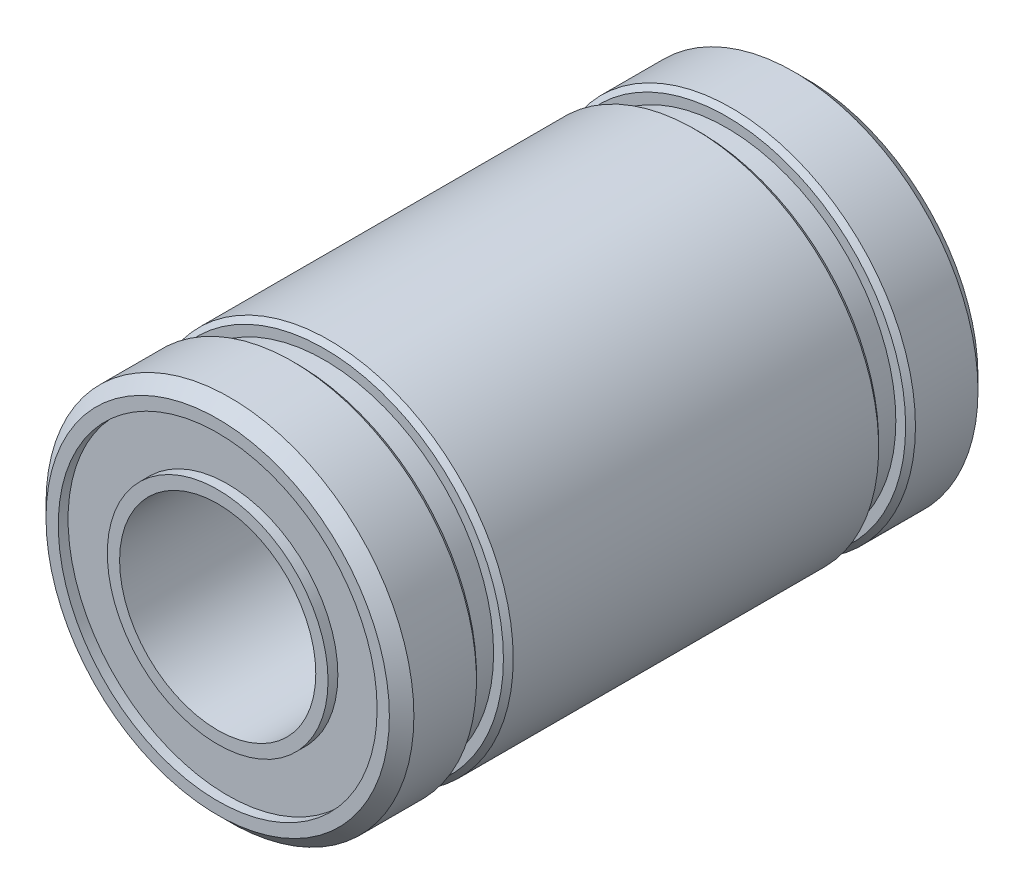
SolidWorks part; units mm, degrees
ref_plane "Front Plane" through (0, 0, 0) normal (0, 0, 1) x (1, 0, 0)
ref_plane "Top Plane" through (0, 0, 0) normal (0, 1, 0) x (1, 0, 0)
ref_plane "Right Plane" through (0, 0, 0) normal (1, 0, 0) x (0, 0, -1)
sketch "Sketch1" plane through (0, 0, 0) normal (0, 0, 1) x (1, 0, 0)
  circle A0 centre (0, 0) radius 4
  circle A1 centre (0, 0) radius 7.5
  dimension "D1" = 8
  dimension "D2" = 15
extrude "Boss-Extrude1" add sketch "Sketch1" along normal blind 24
sketch "Sketch2" plane through (0, 0, 24) normal (0, 0, 1) x (1, 0, 0)
  circle A0 centre (0, 0) radius 4.5
  circle A1 centre (0, 0) radius 6.5
  dimension "D1" = 13
  dimension "9" = 9
extrude "Cut-Extrude1" cut sketch "Sketch2" against normal blind 0.4
ref_plane "Plane1" through (0, 0, 12) normal (0, 0, 1) x (1, 0, 0)
mirror "Mirror1" about plane through (0, 0, 12) normal (0, 0, 1) of "Cut-Extrude1"
sketch "Sketch3" plane through (0, 0, 0) normal (1, 0, 0) x (0, 0, -1)
  line L0 (0, 7.5) -> (-24, 7.5) construction
  line L1 (-20.75, 7.5) -> (-19.65, 7.5)
  line L2 (-20.75, 7.5) -> (-20.75, 6.9)
  line L3 (-20.75, 6.9) -> (-19.65, 6.9)
  line L4 (-19.65, 7.5) -> (-19.65, 6.9)
  line L5 (-24, 7.5) -> (-24, -7.5) construction
  line L6 (0, -7.5) -> (0, 7.5) construction
  line L7 (-4.35, 7.5) -> (-3.25, 7.5)
  line L8 (-4.35, 7.5) -> (-4.35, 6.9)
  line L9 (-4.35, 6.9) -> (-3.25, 6.9)
  line L10 (-3.25, 7.5) -> (-3.25, 6.9)
  point P8 (-20.75, 7.2)
  dimension "D1" = 0.6
  dimension "D2" = 3.25
  dimension "1.1." = 1.1
  dimension "D3" = 0.6
  dimension "D4" = 1.1
  dimension "D5" = 3.25
revolve "Cut-Revolve1" cut sketch "Sketch3" angle 360 about axis through (0, 0, 24) along (0, 0, -1)
chamfer "Chamfer1" distance 0.5 angle 45 2 edges at (7.5, 0, 0) (7.5, 0, 24)
chamfer "Chamfer2" distance 0.2 angle 45 4 edges at (7.5, 0, 3.25) (7.5, 0, 4.35) (7.5, 0, 19.65) (7.5, 0, 20.75)
